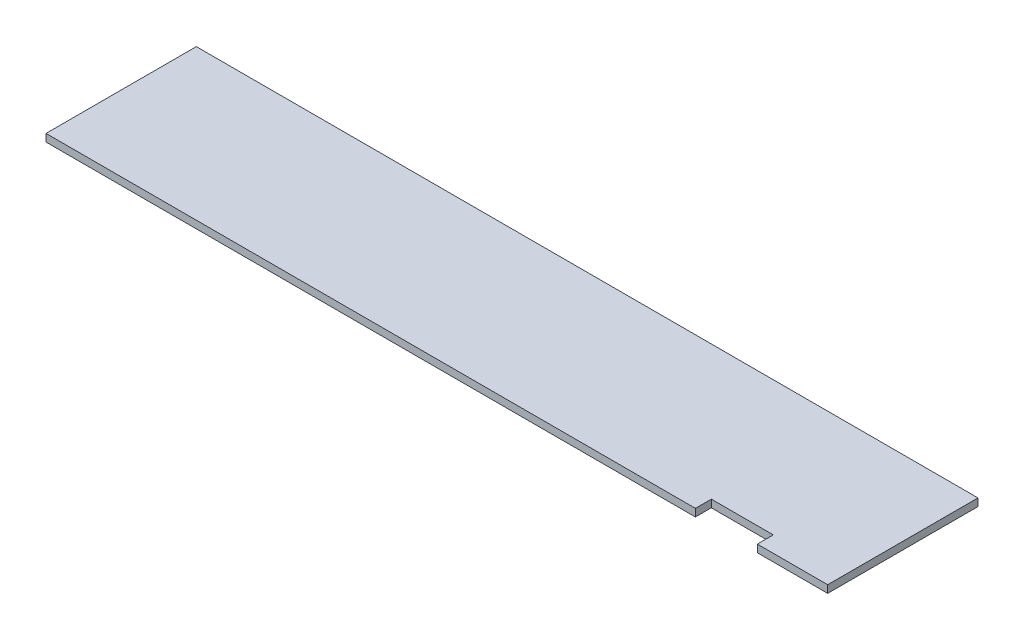
SolidWorks part; units mm, degrees
material "Custom Plastic"
ref_plane "X-Y Datum" through (0, 0, 0) normal (0, 0, 1) x (1, 0, 0)
ref_plane "X-Z Datum" through (0, 0, 0) normal (0, 1, 0) x (1, 0, 0)
ref_plane "Y-Z Datum" through (0, 0, 0) normal (1, 0, 0) x (0, 0, -1)
ref_plane "Plane1" through (0, 0, 0) normal (0, 1, 0) x (1, 0, 0)
sketch "Sketch3" plane through (0, 0, 0) normal (0, 1, 0) x (1, 0, 0)
  line L16 (1643.3038, -343.281) -> (1617.1418, -343.281)
  line L17 (1643.3038, -343.281) -> (1643.3038, -317.119)
  line L18 (1643.3038, -317.119) -> (1617.1418, -317.119)
  line L19 (1617.1418, -343.281) -> (1617.1418, -317.119)
  line L20 (1643.3038, -343.281) -> (1617.1418, -317.119) construction
  line L21 (1643.3038, -317.119) -> (1617.1418, -343.281) construction
  line L24 (1342.8218, -260.35) -> (1342.8218, -323.85)
  line L25 (1342.8218, -260.35) -> (1673.0218, -260.35)
  line L26 (1342.8218, -323.85) -> (1673.0218, -323.85)
  line L27 (1673.0218, -323.85) -> (1673.0218, -260.35)
  point P0 (1630.2228, -330.2)
  point P1 (1630.2228, -330.2)
  dimension "D1" = 26.162
  dimension "D2" = 330.2
extrude "Boss-Extrude1" add sketch "Sketch3" along normal mid plane 3.175 contours L26 L27 L25 L24 L19 L18 L17
